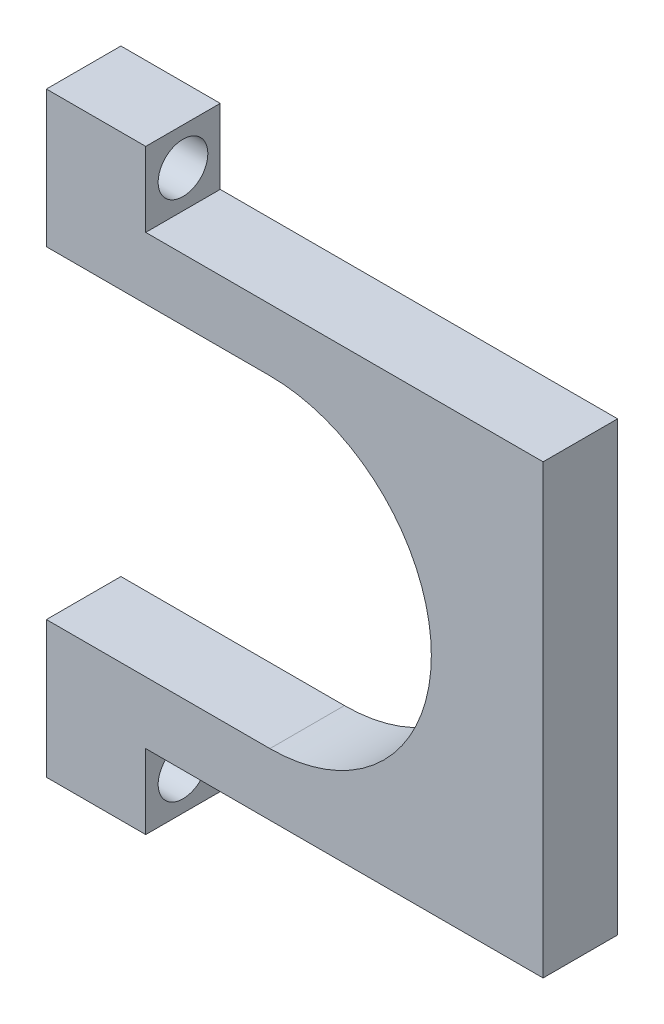
SolidWorks part; units mm, degrees
ref_plane "Front Plane" through (0, 0, 0) normal (0, 0, 1) x (1, 0, 0)
ref_plane "Top Plane" through (0, 0, 0) normal (0, 1, 0) x (1, 0, 0)
ref_plane "Right Plane" through (0, 0, 0) normal (1, 0, 0) x (0, 0, -1)
sketch "Sketch2" plane through (0, 0, 0) normal (0, 0, 1) x (1, 0, 0)
  line L0 (-11.557, -12.3339) -> (8.443, -12.3339)
  line L1 (-11.557, 5.6661) -> (8.443, 5.6661)
  line L2 (-11.557, 5.6661) -> (-11.557, 3.1661)
  line L4 (8.443, 5.6661) -> (8.443, -12.3339)
  line L5 (-11.557, 3.1661) -> (-2.557, 3.1661)
  line L6 (-2.557, -9.8339) -> (-11.557, -9.8339)
  line L7 (-11.557, -9.8339) -> (-11.557, -12.3339)
  arc A0 (-2.557, -9.8339) -> (-2.557, 3.1661) centre (-2.557, -3.3339) ccw
  dimension "D4" = 13
  dimension "D1" = 20
  dimension "D2" = 20
  dimension "D5" = 11
  dimension "D7" = 2.5
  dimension "D9" = 2.5
extrude "Boss-Extrude1" add sketch "Sketch2" against normal blind 3
sketch "Sketch3" plane through (0, 5.6661, 0) normal (0, 1, 0) x (1, 0, 0)
  line L0 (8.443, 3) -> (-11.557, 3) construction
  line L1 (-11.557, 3) -> (-7.557, 3)
  line L2 (-11.557, 3) -> (-11.557, 0)
  line L3 (-11.557, 0) -> (-7.557, 0)
  line L4 (-7.557, 3) -> (-7.557, 0)
  line L5 (-11.557, 3) -> (-11.557, 0) construction
  line L6 (8.443, 0) -> (-11.557, 0) construction
  dimension "D1" = 4
extrude "Boss-Extrude2" add sketch "Sketch3" along normal blind 3
sketch "Sketch4" plane through (0, -12.3339, 0) normal (0, -1, 0) x (1, 0, 0)
  line L0 (-11.557, -3) -> (8.443, -3) construction
  line L1 (-11.557, 0) -> (-7.557, 0)
  line L2 (-11.557, 0) -> (-11.557, -3)
  line L3 (-11.557, -3) -> (-7.557, -3)
  line L4 (-7.557, 0) -> (-7.557, -3)
  dimension "D1" = 4
extrude "Boss-Extrude3" add sketch "Sketch4" along normal blind 3
sketch "Sketch5" plane through (-7.557, 0, 0) normal (1, 0, 0) x (0, 0, -1)
  line L0 (3, 8.6661) -> (3, 5.6661) construction
  line L1 (0, 8.6661) -> (3, 8.6661) construction
  circle A0 centre (1.5, 7.1661) radius 1
  dimension "D1" = 2
  dimension "D2" = 1.5
  dimension "D3" = 1.5
extrude "Cut-Extrude1" cut sketch "Sketch5" against normal through all
sketch "Sketch6" plane through (-7.557, 0, 0) normal (1, 0, 0) x (0, 0, -1)
  line L0 (3, -15.3339) -> (3, -12.3339) construction
  line L2 (3, -15.3339) -> (0, -15.3339) construction
  circle A0 centre (1.5, -13.8339) radius 1
  dimension "D1" = 2
  dimension "D2" = 1.5
  dimension "D3" = 1.5
extrude "Cut-Extrude2" cut sketch "Sketch6" against normal through all
